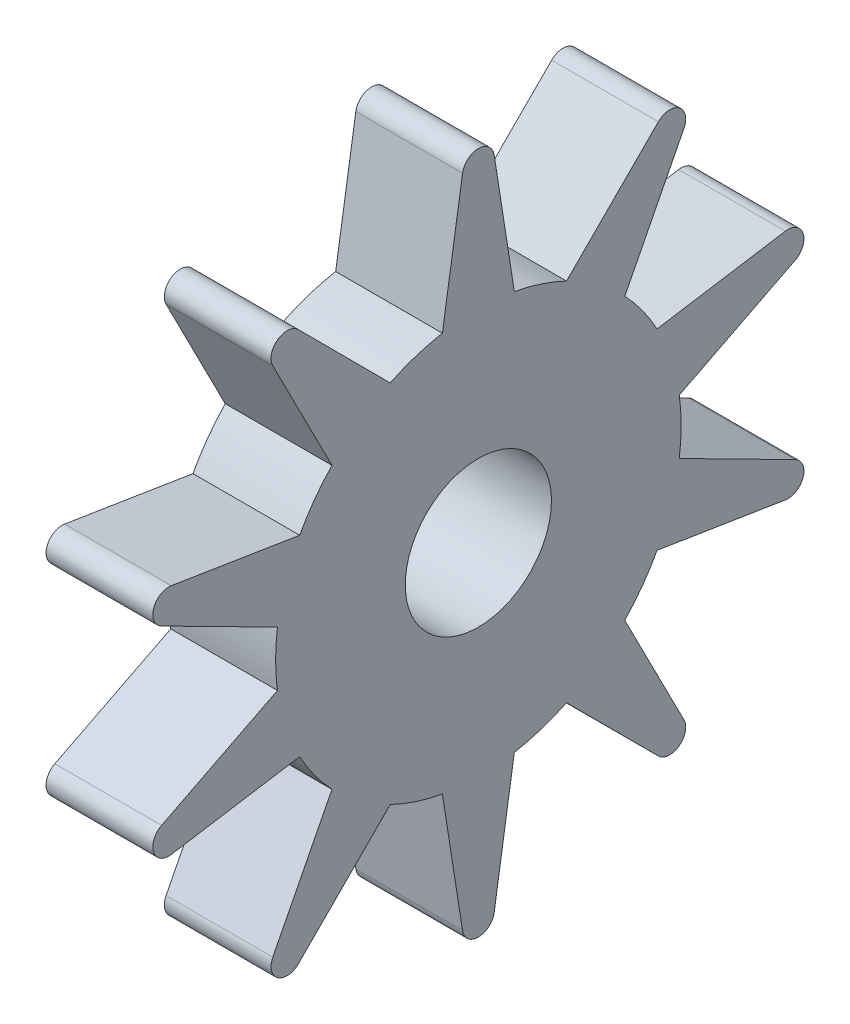
SolidWorks part; units mm, degrees
ref_plane "Front Plane" through (0, 0, 0) normal (0, 0, 1) x (1, 0, 0)
ref_plane "Top Plane" through (0, 0, 0) normal (0, 1, 0) x (1, 0, 0)
ref_plane "Right Plane" through (0, 0, 0) normal (1, 0, 0) x (0, 0, -1)
sketch "Sketch2" plane through (0, 0, 0) normal (1, 0, 0) x (0, 0, -1)
  line L0 (0, 0) -> (0, 3.425)
  line L3 (-0.7424, 15.3563) -> (-1.6, 9.3643)
  line L5 (0.7424, 15.3563) -> (1.6006, 9.3642)
  line L11 (1.6, 9.3686) -> (1.6, 9.3643)
  line L12 (0, 15.25) -> (0, 16)
  circle A6 centre (0, 0) radius 9.5
  arc A7 (0.7424, 15.3563) -> (-0.7424, 15.3563) centre (0, 15.25) ccw
  circle A8 centre (0, 0) radius 3.425
  dimension "D2" = 19
  dimension "D3" = 1.5
  dimension "D6" = 6.85
extrude "Boss-Extrude3" add sketch "Sketch2" along normal blind 5 contours A6 | A8
sketch "Sketch4" plane through (0, 0, 0) normal (-1, 0, 0) x (0, 0, 1)
  line L0 (0, 0) -> (0, 8.618)
  line L1 (-0.7409, 15.3663) -> (-1.6852, 9.3493)
  line L3 (0.7409, 15.3663) -> (1.6852, 9.3493)
  arc A0 (0.7409, 15.3663) -> (-0.7409, 15.3663) centre (0, 15.25) ccw
  circle A2 centre (0, 0) radius 9.5
  arc A3 (1.6852, 9.3493) -> (-1.6852, 9.3493) centre (0, 0) ccw
  dimension "D2" = 1.5
  dimension "D1" = 15.25
  dimension "D5" = 0
extrude "Boss-Extrude5" add sketch "Sketch4" against normal blind 5 contours L3 A3 L1 A0
pattern_circular "CirPattern1" count 10 over 360 about axis through (0, 0, 0) along (1, 0, 0) of "Boss-Extrude5"
